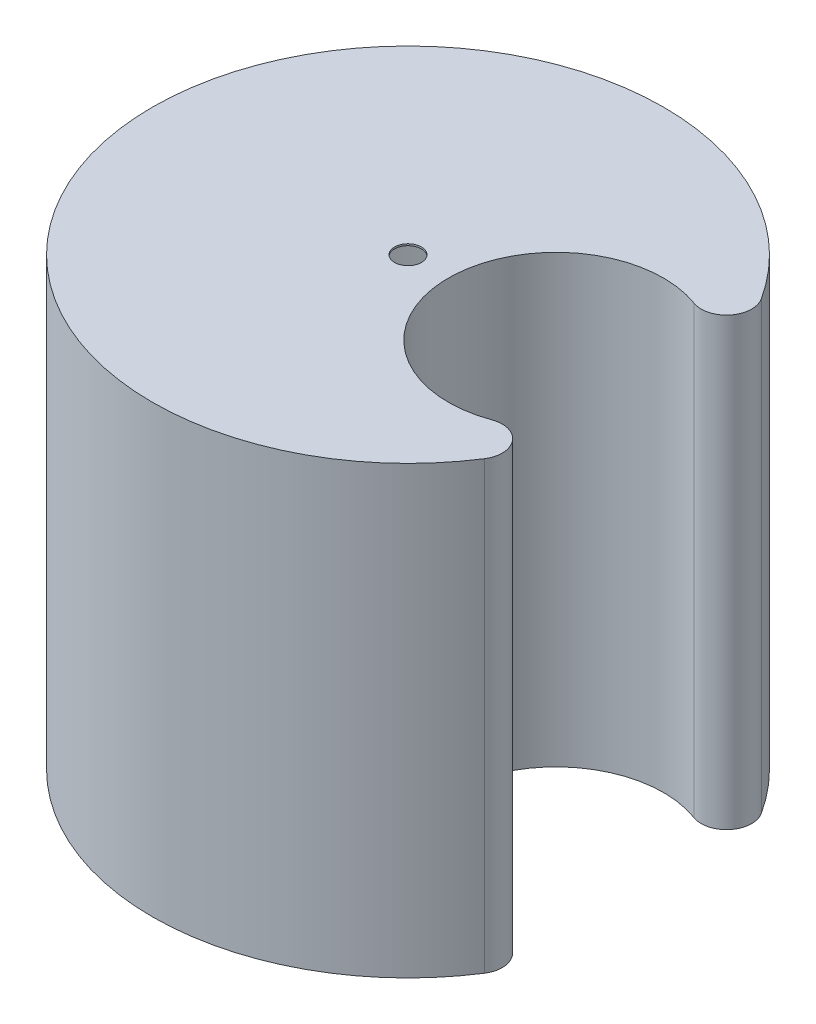
SolidWorks part; units mm, degrees
ref_plane "Front Plane" through (0, 0, 0) normal (0, 0, 1) x (1, 0, 0)
ref_plane "Top Plane" through (0, 0, 0) normal (0, 1, 0) x (1, 0, 0)
ref_plane "Right Plane" through (0, 0, 0) normal (1, 0, 0) x (0, 0, -1)
sketch "Sketch1" plane through (0, 0, 0) normal (0, 0, 1) x (1, 0, 0)
  line L0 (0, 0) -> (0, 120.6694) construction
  line L1 (0, 105.1719) -> (60.325, 105.1719)
  line L2 (60.325, 105.1719) -> (60.325, 0)
  line L3 (60.325, 0) -> (59.9281, 0)
  line L4 (59.9281, 0) -> (59.9281, 104.775) construction
  line L5 (59.9281, 104.775) -> (0, 104.775) construction
  line L6 (0, 104.775) -> (0, 105.1719) construction
  line L7 (0, 130.5719) -> (60.325, 130.5719) construction
  line L8 (59.9281, 0) -> (0, 0)
  line L9 (0, 0) -> (0, 105.1719)
  dimension "D1" = 120.65
  dimension "D2" = 0.3969
  dimension "D3" = 104.775
  dimension "D4" = 25.4
  dimension "D5" = 130.5719
revolve "Revolve1" add sketch "Sketch1" angle 360 about L0
sketch "Sketch2" plane through (0, 105.1719, 0) normal (0, 1, 0) x (1, 0, 0)
  circle A0 centre (0, 0) radius 3.175 construction
  arc A1 (43.6645, 23.8491) -> (43.6645, -23.8491) centre (34.925, 0) ccw
  arc A2 (50.7178, -32.662) -> (50.7178, 32.662) centre (0, 0) ccw
  circle A3 centre (0, 0) radius 60.325 construction
  arc A4 (43.6645, 23.8491) -> (50.7178, 32.662) centre (45.7128, 29.4388) ccw
  arc A5 (43.6645, -23.8491) -> (50.7178, -32.662) centre (45.7128, -29.4388) cw
  dimension "D1" = 6.35
  dimension "D2" = 50.8
  dimension "D3" = 34.925
  dimension "D4" = 5.9531
extrude "Cut-Extrude1" cut sketch "Sketch2" against normal through all
fillet "Fillet1" [suppressed] radius 6.35
shell "Shell1" thickness 0.3969
sketch "Sketch3" plane through (0, 104.775, 0) normal (0, -1, 0) x (1, 0, 0)
  circle A0 centre (0, 0) radius 3.175
  dimension "D1" = 6.35
extrude "Cut-Extrude2" cut sketch "Sketch3" against normal through all
